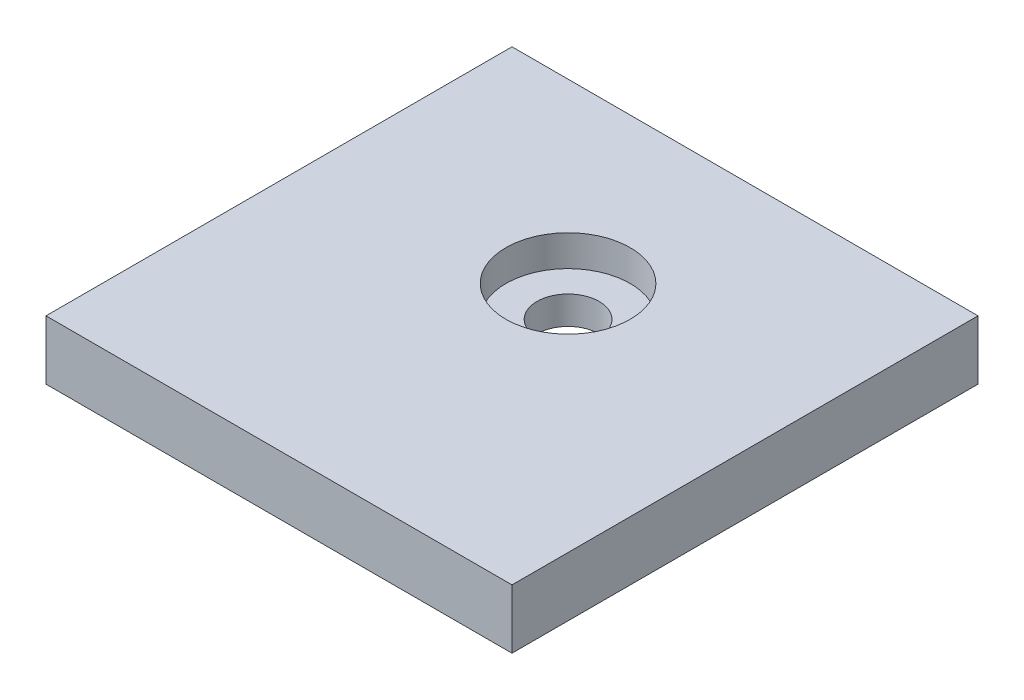
SolidWorks part; units mm, degrees
ref_plane "Alzado" through (0, 0, 0) normal (0, 0, 1) x (1, 0, 0)
ref_plane "Planta" through (0, 0, 0) normal (0, 1, 0) x (1, 0, 0)
ref_plane "Vista lateral" through (0, 0, 0) normal (1, 0, 0) x (0, 0, -1)
sketch "Croquis1" plane through (0, 0, 0) normal (0, 1, 0) x (1, 0, 0)
  line L1 (37.5, -37.5) -> (-37.5, -37.5)
  line L2 (37.5, -37.5) -> (37.5, 37.5)
  line L3 (37.5, 37.5) -> (-37.5, 37.5)
  line L4 (-37.5, -37.5) -> (-37.5, 37.5)
  line L5 (37.5, -37.5) -> (-37.5, 37.5) construction
  line L6 (37.5, 37.5) -> (-37.5, -37.5) construction
  circle A0 centre (0, 9.0223) radius 5
  point P0 (0, 0)
  dimension "D2" = 10
  dimension "D1" = 75
extrude "Saliente-Extruir1" add sketch "Croquis1" along normal blind 9.525
sketch "Croquis2" plane through (0, 9.525, 0) normal (0, 1, 0) x (1, 0, 0)
  circle A0 centre (0, 9.0223) radius 10
  dimension "D1" = 20
extrude "Cortar-Extruir1" cut sketch "Croquis2" against normal blind 5
